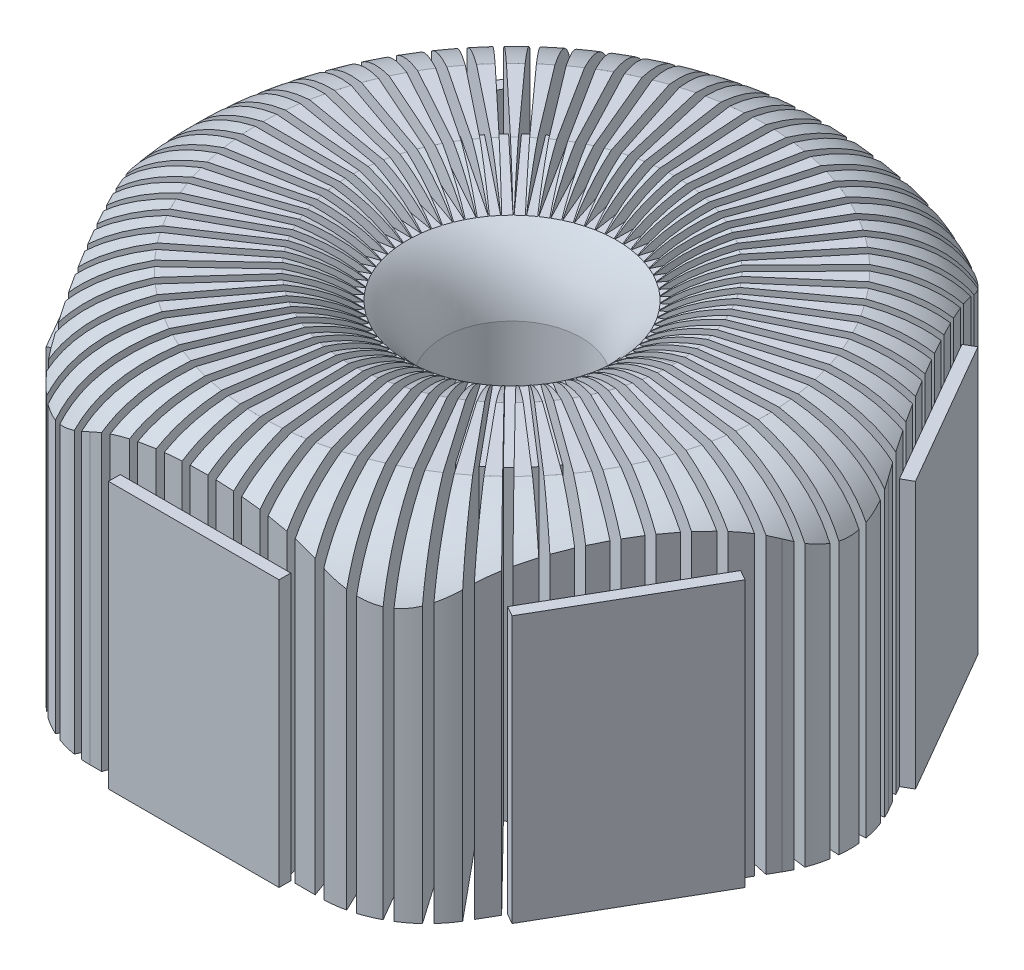
SolidWorks part; units mm, degrees
ref_plane "Front Plane" through (0, 0, 0) normal (0, 0, 1) x (1, 0, 0)
ref_plane "Top Plane" through (0, 0, 0) normal (0, 1, 0) x (1, 0, 0)
ref_plane "Right Plane" through (0, 0, 0) normal (1, 0, 0) x (0, 0, -1)
sketch "Sketch1" plane through (0, 0, 0) normal (0, 1, 0) x (1, 0, 0)
  line L1 (60.6218, 10) -> (38.9711, 47.5)
  line L2 (21.6506, 57.5) -> (-21.6506, 57.5)
  line L3 (-38.9711, 47.5) -> (-60.6218, 10)
  line L4 (-60.6218, -10) -> (-38.9711, -47.5)
  line L5 (-21.6506, -57.5) -> (21.6506, -57.5)
  line L6 (38.9711, -47.5) -> (60.6218, -10)
  circle A0 centre (0, 0) radius 57.5 construction
  arc A1 (-21.6506, -57.5) -> (-38.9711, -47.5) centre (-21.6506, -37.5) cw
  arc A2 (21.6506, -57.5) -> (38.9711, -47.5) centre (21.6506, -37.5) ccw
  arc A3 (60.6218, -10) -> (60.6218, 10) centre (43.3013, 0) ccw
  arc A4 (38.9711, 47.5) -> (21.6506, 57.5) centre (21.6506, 37.5) ccw
  arc A5 (-21.6506, 57.5) -> (-38.9711, 47.5) centre (-21.6506, 37.5) ccw
  arc A6 (-60.6218, -10) -> (-60.6218, 10) centre (-43.3013, 0) cw
  dimension "D1" = 115
  dimension "D2" = 20
extrude "Boss-Extrude2" add sketch "Sketch1" along normal blind 62.5
sketch "Sketch6" plane through (0, 62.5, 0) normal (0, 1, 0) x (1, 0, 0)
  circle A0 centre (0, 0) radius 13
extrude "Cut-Extrude1" cut sketch "Sketch6" against normal up to surface (62.5 mm away) up to face at (0, 0, 0)
sketch "Sketch7" plane through (0, 0, 0) normal (0, 0, 1) x (1, 0, 0)
  line L0 (0, 62.5) -> (0, 0) construction
  line L1 (-21.6506, 62.5) -> (21.6506, 62.5) construction
  line L2 (0, 62.5) -> (13, 62.5) construction
  line L3 (13, 62.5) -> (13, 45)
  line L4 (13, 62.5) -> (30.5, 62.5)
  line L5 (38.9711, 62.5) -> (21.6506, 62.5) construction
  line L6 (13, 0) -> (63.3013, 0) construction
  line L7 (38.9711, 0) -> (38.9711, 62.5) construction
  line L8 (64.9423, 62.5) -> (47.4423, 62.5)
  line L9 (64.9423, 62.5) -> (64.9423, 45)
  line L10 (13, 62.5) -> (-13, 62.5) construction
  line L11 (13, 62.5) -> (18.1614, 56.1261) construction
  spline S0 degree 2 poles (13, 45) (15.1116, 59.0525) (30.5, 62.5) knots 0 0 0 1 1 1
  spline S1 degree 2 poles (64.9423, 45) (62.8306, 59.0525) (47.4423, 62.5) knots 0 0 0 1 1 1
  dimension "D1" = 13
  dimension "D2" = 17.5
  dimension "D3" = 17.5
  dimension "D4" = 8.2017
revolve "Cut-Revolve1" cut sketch "Sketch7" angle 360 about L0
ref_plane "Plane1" through (0, 31.25, 0) normal (0, 1, 0) x (1, 0, 0)
sketch "Sketch8" plane through (0, 0, 0) normal (0, 0, 1) x (1, 0, 0)
  line L0 (-63.3013, 62.5) -> (-63.3013, 0)
  line L1 (-13.3013, 5) -> (-38.3013, 5) construction
  line L2 (-38.3013, 5) -> (-38.3013, 0)
  line L3 (-63.3013, 0) -> (-38.3013, 0)
  line L4 (-13.3013, 0) -> (-13.3013, 5) construction
  line L5 (-38.3013, 5) -> (-38.3013, 57.5)
  line L6 (63.25, 31.25) -> (-63.25, 31.25) construction
  line L7 (-63.3013, 31.25) -> (-38.3013, 31.25) construction
  line L8 (-13.3013, 62.5) -> (-13.3013, 57.5)
  line L9 (-63.3013, 62.5) -> (-13.3013, 62.5)
  line L10 (-13.3013, 57.5) -> (-38.3013, 57.5)
  line L11 (-38.3013, 0) -> (-13.3013, 0) construction
  point P3 (-66.188, 24)
  dimension "D1" = 50
  dimension "D2" = 50
  dimension "D3" = 5
  dimension "D4" = 25
extrude "Cut-Extrude2" cut sketch "Sketch8" against normal blind 0.75 and the other way blind 0.75
pattern_circular "CirPattern1" count 75 over 360 about axis through (0, 0, 0) along (0, 1, 0) of "Cut-Extrude2"
sketch "Sketch9" plane through (0, 0, 0) normal (0, 1, 0) x (1, 0, 0)
  line L0 (0, 0) -> (0, 57.5) construction
  line L1 (0.4543, 57.5) -> (-2.8661, 57.5) construction
  line L2 (16, 57.5) -> (-16, 57.5)
  line L3 (0, 57.5) -> (0, 59.7)
  line L4 (-16, 57.5) -> (-16, 59.7)
  line L5 (16, 59.7) -> (-16, 59.7)
  line L7 (16, 57.5) -> (16, 59.7)
  line L8 (57.7965, 14.8936) -> (41.7965, 42.6064)
  line L9 (59.7017, 15.9936) -> (43.7017, 43.7064)
  line L10 (57.7965, 14.8936) -> (59.7017, 15.9936)
  line L11 (41.7965, 42.6064) -> (43.7017, 43.7064)
  line L12 (41.7965, -42.6064) -> (57.7965, -14.8936)
  line L13 (43.7017, -43.7064) -> (59.7017, -15.9936)
  line L14 (41.7965, -42.6064) -> (43.7017, -43.7064)
  line L15 (57.7965, -14.8936) -> (59.7017, -15.9936)
  line L16 (-16, -57.5) -> (16, -57.5)
  line L17 (-16, -59.7) -> (16, -59.7)
  line L18 (-16, -57.5) -> (-16, -59.7)
  line L19 (16, -57.5) -> (16, -59.7)
  line L20 (-57.7965, -14.8936) -> (-41.7965, -42.6064)
  line L21 (-59.7017, -15.9936) -> (-43.7017, -43.7064)
  line L22 (-57.7965, -14.8936) -> (-59.7017, -15.9936)
  line L23 (-41.7965, -42.6064) -> (-43.7017, -43.7064)
  line L24 (-41.7965, 42.6064) -> (-57.7965, 14.8936)
  line L25 (-43.7017, 43.7064) -> (-59.7017, 15.9936)
  line L26 (-41.7965, 42.6064) -> (-43.7017, 43.7064)
  line L27 (-57.7965, 14.8936) -> (-59.7017, 15.9936)
  point P10 (0, 0)
  point P11 (0, 0)
  point P33 (0, 0)
  dimension "D1" = 2.2
  dimension "D2" = 16
  dimension "D3" = 6
extrude "Boss-Extrude3" add sketch "Sketch9" along normal blind 50 contours L3 L5 L4 L2 | L2 L7 L5 L3 | L17 L19 L16 L18 | L21 L23 L20 L22 | L25 L27 L24 L26 | L8 L11 L9 L10 | L13 L15 L12 L14
